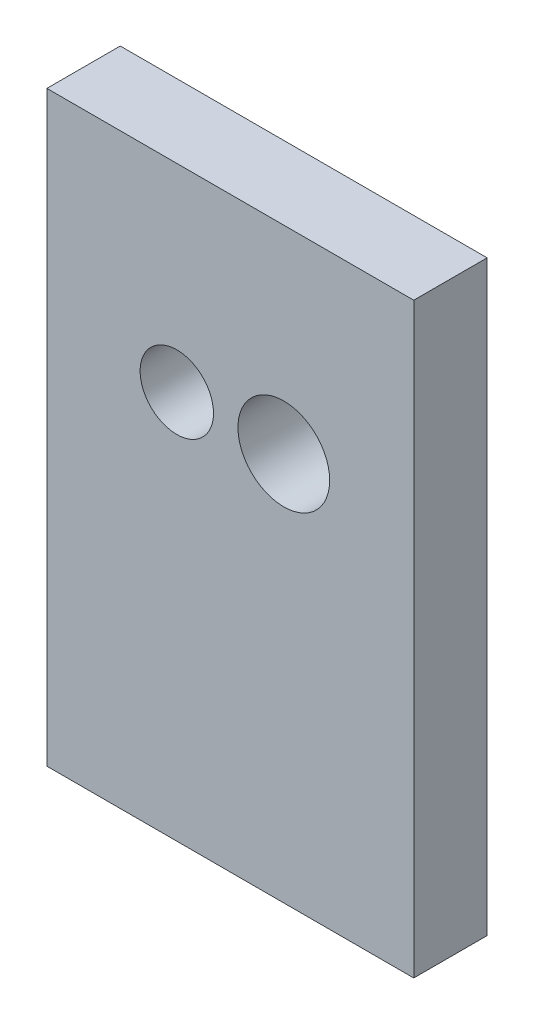
SolidWorks part; units mm, degrees
material "Acrylic (Medium-high impact)"
ref_plane "Front Plane" through (0, 0, 0) normal (0, 0, 1) x (1, 0, 0)
ref_plane "Top Plane" through (0, 0, 0) normal (0, 1, 0) x (1, 0, 0)
ref_plane "Right Plane" through (0, 0, 0) normal (1, 0, 0) x (0, 0, -1)
sketch "Sketch1" plane through (0, 0, 0) normal (0, 0, 1) x (1, 0, 0)
  line L0 (0, 0) -> (-9.2608, 0) construction
  line L1 (-31.75, 67.31) -> (31.75, 67.31)
  line L2 (-31.75, 67.31) -> (-31.75, -67.31)
  line L3 (-31.75, -67.31) -> (31.75, -67.31)
  line L4 (31.75, 67.31) -> (31.75, -67.31)
  line L5 (-31.75, 67.31) -> (31.75, -67.31) construction
  line L6 (-31.75, -67.31) -> (31.75, 67.31) construction
  line L7 (0, 0) -> (9.2608, 0)
  circle A0 centre (-9.2608, 0) radius 6.35
  circle A1 centre (9.2608, 0) radius 7.9375
  point P0 (0, 0)
  dimension "D5" = 15.875
  dimension "D6" = 12.7
  dimension "D1" = 63.5
  dimension "D2" = 134.62
  dimension "D3" = 9.2608
  dimension "D4" = 9.2608
extrude "Boss-Extrude1" add sketch "Sketch1" along normal blind 12.7
sketch "Sketch2" plane through (0, 0, 12.7) normal (0, 0, 1) x (1, 0, 0)
  line L0 (31.75, 67.31) -> (31.75, -67.31) construction
  line L1 (-31.75, 67.31) -> (31.75, 67.31)
  line L2 (-31.75, 67.31) -> (-31.75, 34.29)
  line L3 (-31.75, 34.29) -> (31.75, 34.29)
  line L4 (31.75, 67.31) -> (31.75, 34.29)
  dimension "D1" = 33.02
extrude "Cut-Extrude1" cut sketch "Sketch2" against normal through all
